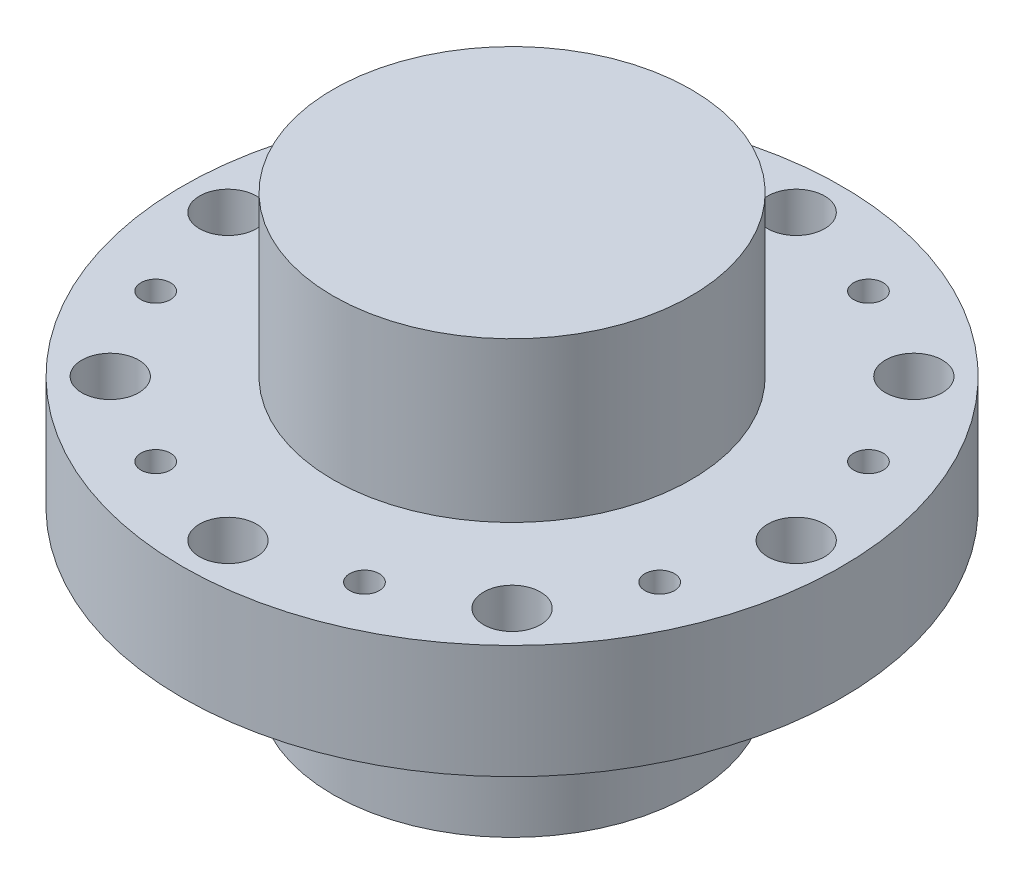
SolidWorks part; units mm, degrees
material "6061-T6 (SS)"
ref_plane "Front Plane" through (0, 0, 0) normal (0, 0, 1) x (1, 0, 0)
ref_plane "Top Plane" through (0, 0, 0) normal (0, 1, 0) x (1, 0, 0)
ref_plane "Right Plane" through (0, 0, 0) normal (1, 0, 0) x (0, 0, -1)
sketch "Sketch1" plane through (0, 0, 0) normal (0, 1, 0) x (1, 0, 0)
  circle A0 centre (0, 0) radius 15.75
extrude "Boss-Extrude1" add sketch "Sketch1" along normal blind 14
sketch "Sketch2" plane through (0, 14, 0) normal (0, 1, 0) x (1, 0, 0)
  circle A0 centre (0, 0) radius 29
extrude "Boss-Extrude2" add sketch "Sketch2" along normal blind 10 contours A0
sketch "Sketch4" plane through (0, 24, 0) normal (0, 1, 0) x (1, 0, 0)
  line L0 (0, 0) -> (0, 37.1279) construction
  circle A0 centre (0, 25) radius 2.5
  point P3 (0, 25)
  dimension "D2" = 5
  dimension "D1" = 25
extrude "Cut-Extrude1" cut sketch "Sketch4" against normal blind 5
sketch "Sketch5" plane through (0, 19, 0) normal (0, 1, 0) x (1, 0, 0)
  circle A0 centre (0, 25) radius 1.295
extrude "Cut-Extrude2" cut sketch "Sketch5" against normal through all
pattern_circular "CirPattern1" count 8 over 360 about axis through (0, 0, 0) along (0, 1, 0) of "Cut-Extrude1", "Cut-Extrude2"
sketch "Sketch6" plane through (0, 24, 0) normal (0, 1, 0) x (1, 0, 0)
  circle A0 centre (0, 0) radius 15.75
  dimension "D1" = 31.5
extrude "Boss-Extrude3" add sketch "Sketch6" along normal blind 14
sketch "Sketch7" plane through (0, 0, 0) normal (0, 1, 0) x (1, 0, 0)
  circle A0 centre (22.1731, -9.1844) radius 2.75
  circle A1 centre (9.1844, -22.1731) radius 2.75
  circle A2 centre (-9.1844, -22.1731) radius 2.75
  circle A3 centre (-22.1731, -9.1844) radius 2.75
  circle A4 centre (-22.1731, 9.1844) radius 2.75
  circle A5 centre (-9.1844, 22.1731) radius 2.75
  circle A6 centre (9.1844, 22.1731) radius 2.75
  circle A7 centre (22.1731, 9.1844) radius 2.75
sketch "Sketch8" plane through (0, 0, 0) normal (0, 1, 0) x (1, 0, 0)
  circle A0 centre (22.1731, -9.1844) radius 4.75
  circle A1 centre (9.1844, -22.1731) radius 4.75
  circle A2 centre (-9.1844, -22.1731) radius 4.75
  circle A3 centre (-22.1731, -9.1844) radius 4.75
  circle A4 centre (-22.1731, 9.1844) radius 4.75
  circle A5 centre (-9.1844, 22.1731) radius 4.75
  circle A6 centre (9.1844, 22.1731) radius 4.75
  circle A7 centre (22.1731, 9.1844) radius 4.75
sketch "Sketch9" plane through (0, 0, 0) normal (0, 1, 0) x (1, 0, 0)
  circle A0 centre (22.1731, -9.1844) radius 1.3
  circle A1 centre (9.1844, -22.1731) radius 1.3
  circle A2 centre (-9.1844, -22.1731) radius 1.3
  circle A3 centre (-22.1731, -9.1844) radius 1.3
  circle A4 centre (-22.1731, 9.1844) radius 1.3
  circle A5 centre (-9.1844, 22.1731) radius 1.3
  circle A6 centre (9.1844, 22.1731) radius 1.3
  circle A7 centre (22.1731, 9.1844) radius 1.3
extrude "LoBac-M25-Through-x8" cut sketch "Sketch9" along normal blind 10 from offset 14
sketch "Sketch10" plane through (0, 0, 0) normal (0, 1, 0) x (1, 0, 0)
  circle A0 centre (22.1731, -9.1844) radius 2.5
  circle A1 centre (9.1844, -22.1731) radius 2.5
  circle A2 centre (-9.1844, -22.1731) radius 2.5
  circle A3 centre (-22.1731, -9.1844) radius 2.5
  circle A4 centre (-22.1731, 9.1844) radius 2.5
  circle A5 centre (-9.1844, 22.1731) radius 2.5
  circle A6 centre (9.1844, 22.1731) radius 2.5
  circle A7 centre (22.1731, 9.1844) radius 2.5
extrude "LoBac-M25-CBore-x8" cut sketch "Sketch10" along normal blind 5 from offset 14
